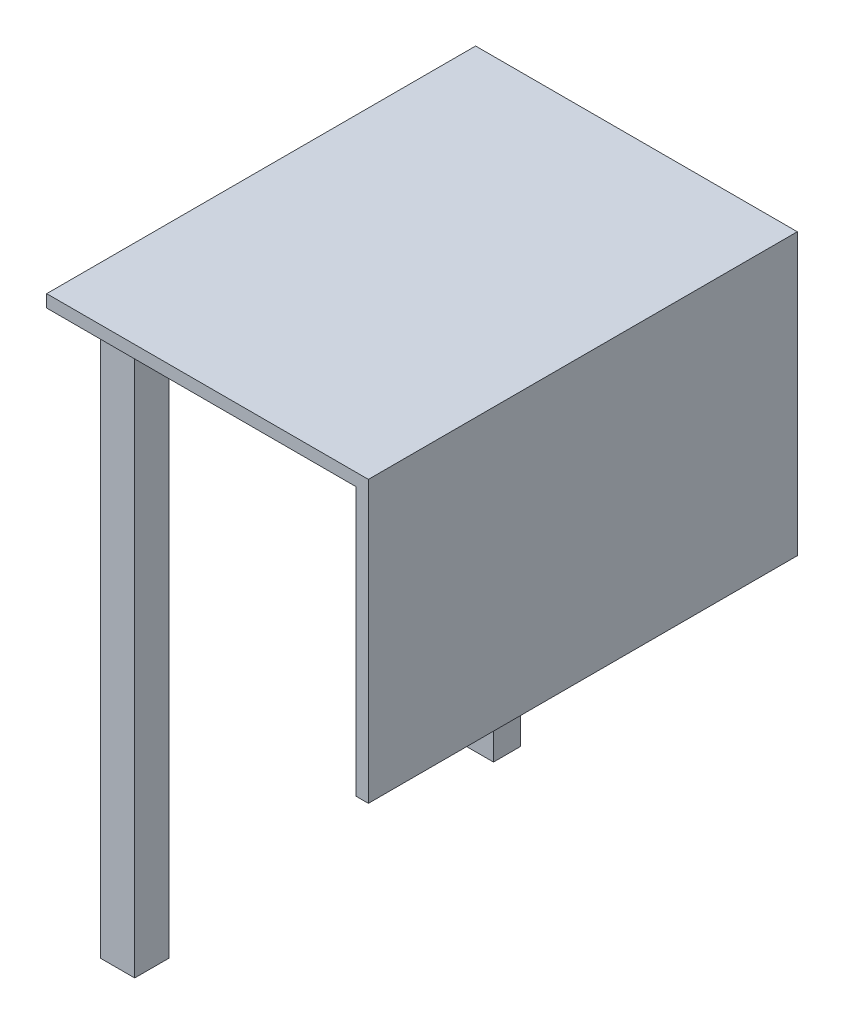
SolidWorks part; units mm, degrees
ref_plane "Front Plane" through (0, 0, 0) normal (0, 0, 1) x (1, 0, 0)
ref_plane "Top Plane" through (0, 0, 0) normal (0, 1, 0) x (1, 0, 0)
ref_plane "Right Plane" through (0, 0, 0) normal (1, 0, 0) x (0, 0, -1)
sketch "Sketch2" plane through (0, 0, 0) normal (0, 1, 0) x (1, 0, 0)
  line L0 (210.82, 304.8) -> (210.82, -304.8) construction
  line L1 (-228.6, 304.8) -> (228.6, 304.8)
  line L2 (-228.6, 304.8) -> (-228.6, -304.8)
  line L3 (-228.6, -304.8) -> (228.6, -304.8)
  line L4 (228.6, 304.8) -> (228.6, -304.8)
  line L5 (-228.6, 304.8) -> (228.6, -304.8) construction
  line L6 (-228.6, -304.8) -> (228.6, 304.8) construction
  line L8 (-177.8, 279.4) -> (-139.7, 279.4)
  line L9 (-177.8, 279.4) -> (-177.8, 241.3)
  line L10 (-177.8, 241.3) -> (-139.7, 241.3)
  line L11 (-139.7, 279.4) -> (-139.7, 241.3)
  line L12 (-177.8, 279.4) -> (-139.7, 241.3) construction
  line L13 (-177.8, 241.3) -> (-139.7, 279.4) construction
  line L14 (-177.8, -230.5371) -> (-128.9371, -230.5371)
  line L15 (-177.8, -230.5371) -> (-177.8, -279.4)
  line L16 (-177.8, -279.4) -> (-128.9371, -279.4)
  line L17 (-128.9371, -230.5371) -> (-128.9371, -279.4)
  line L18 (-177.8, -230.5371) -> (-128.9371, -279.4) construction
  line L19 (-177.8, -279.4) -> (-128.9371, -230.5371) construction
  point P0 (0, 0)
  point P8 (-158.75, 260.35)
  point P13 (-153.3685, -254.9685)
  dimension "D1" = 609.6
  dimension "D2" = 457.2
  dimension "D3" = 17.78
  dimension "D4" = 38.1
  dimension "D5" = 48.8629
  dimension "D6" = 50.8
  dimension "D7" = 25.4
  dimension "D8" = 50.8
  dimension "D9" = 25.4
extrude "Boss-Extrude1" add sketch "Sketch2" along normal blind 17.78
sketch "Sketch3" plane through (0, 0, 0) normal (0, 1, 0) x (1, 0, 0)
  line L0 (210.82, 304.8) -> (210.82, -304.8) construction
  line L1 (210.82, 304.8) -> (210.82, -304.8)
  line L2 (228.6, 304.8) -> (228.6, -304.8) construction
  line L3 (228.6, 304.8) -> (228.6, -304.8)
  line L4 (210.82, 304.8) -> (228.6, 304.8)
  line L5 (228.6, -304.8) -> (210.82, -304.8)
extrude "Boss-Extrude2" add sketch "Sketch3" against normal blind 381
sketch "Sketch4" plane through (0, 0, 0) normal (0, 1, 0) x (1, 0, 0)
  line L0 (-139.7, 279.4) -> (-139.7, 241.3) construction
  line L1 (-177.8, 241.3) -> (-139.7, 241.3) construction
  line L2 (-177.8, 279.4) -> (-177.8, 241.3) construction
  line L3 (-177.8, 279.4) -> (-139.7, 279.4) construction
  line L4 (-139.7, 279.4) -> (-139.7, 241.3)
  line L5 (-177.8, 241.3) -> (-139.7, 241.3)
  line L6 (-177.8, 279.4) -> (-177.8, 241.3)
  line L7 (-177.8, 279.4) -> (-139.7, 279.4)
  line L8 (-128.9371, -230.5371) -> (-128.9371, -279.4) construction
  line L9 (-177.8, -279.4) -> (-128.9371, -279.4) construction
  line L10 (-177.8, -230.5371) -> (-177.8, -279.4) construction
  line L11 (-177.8, -230.5371) -> (-128.9371, -230.5371) construction
  line L12 (-128.9371, -230.5371) -> (-128.9371, -279.4)
  line L13 (-177.8, -279.4) -> (-128.9371, -279.4)
  line L14 (-177.8, -230.5371) -> (-177.8, -279.4)
  line L15 (-177.8, -230.5371) -> (-128.9371, -230.5371)
extrude "Boss-Extrude3" add sketch "Sketch4" along normal blind 17.78 and the other way blind 787.4
